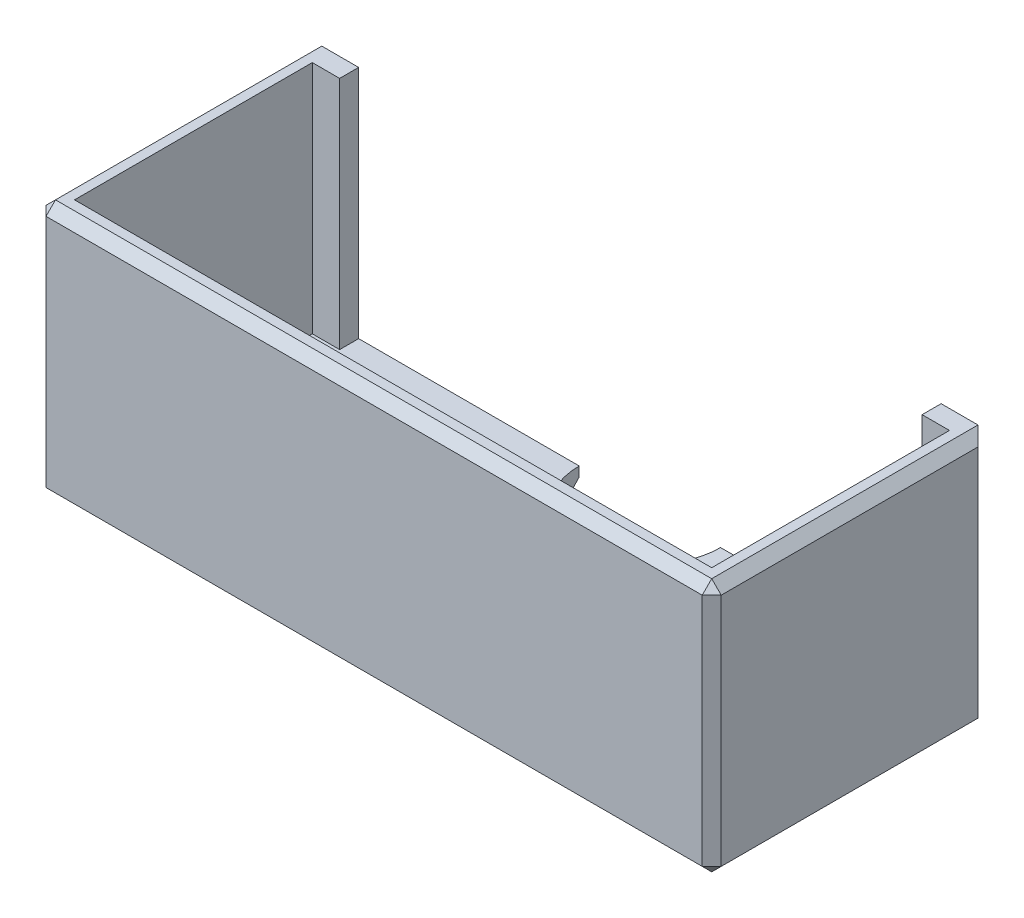
SolidWorks part; units mm, degrees
ref_plane "Front Plane" through (0, 0, 0) normal (0, 0, 1) x (1, 0, 0)
ref_plane "Top Plane" through (0, 0, 0) normal (0, 1, 0) x (1, 0, 0)
ref_plane "Right Plane" through (0, 0, 0) normal (1, 0, 0) x (0, 0, -1)
sketch "Sketch1" plane through (0, 0, 0) normal (0, 1, 0) x (1, 0, 0)
  line L1 (-33.5, -12.5) -> (33.5, -12.5)
  line L2 (-33.5, -12.5) -> (-33.5, 12.5)
  line L3 (-33.5, 12.5) -> (33.5, 12.5)
  line L4 (33.5, -12.5) -> (33.5, 12.5)
  line L5 (-33.5, -12.5) -> (33.5, 12.5) construction
  line L6 (-33.5, 12.5) -> (33.5, -12.5) construction
  point P0 (0, 0)
  dimension "D1" = 67
  dimension "D2" = 25
extrude "Extrude-Thin1" add sketch "Sketch1" against normal blind 24.7 thin
sketch "Sketch2" plane through (0, 0, 0) normal (0, 1, 0) x (1, 0, 0)
  line L0 (33.5, 12.5) -> (-33.5, 12.5) construction
  line L1 (-30.6233, 4.165) -> (30.6233, 4.165)
  line L2 (-30.6233, 4.165) -> (-30.6233, 20.835)
  line L3 (-30.6233, 20.835) -> (30.6233, 20.835)
  line L4 (30.6233, 4.165) -> (30.6233, 20.835)
  line L5 (-30.6233, 4.165) -> (30.6233, 20.835) construction
  line L6 (-30.6233, 20.835) -> (30.6233, 4.165) construction
  point P0 (0, 12.5)
extrude "Cut-Extrude1" cut sketch "Sketch2" against normal through all both and the other way through all
sketch "Sketch3" plane through (0, -24.7, 0) normal (0, -1, 0) x (1, 0, 0)
  line L0 (35.5, 14.5) -> (35.5, -14.5)
  line L12 (33.5, -12.5) -> (30.6233, -12.5)
  line L13 (30.6233, -12.5) -> (30.6233, -14.5)
  line L14 (30.6233, -14.5) -> (35.5, -14.5)
  line L15 (35.5, -14.5) -> (35.5, 14.5)
  line L16 (35.5, 14.5) -> (-35.5, 14.5)
  line L17 (-35.5, 14.5) -> (-35.5, -14.5)
  line L18 (-35.5, -14.5) -> (-30.6233, -14.5)
  line L19 (-30.6233, -14.5) -> (-30.6233, -12.5)
  line L20 (-30.6233, -12.5) -> (-33.5, -12.5)
  line L21 (-33.5, -12.5) -> (-33.5, 12.5)
  line L22 (-33.5, 12.5) -> (33.5, 12.5)
  line L23 (33.5, 12.5) -> (33.5, -12.5)
  line L26 (30.6233, -14.5) -> (35.5, -14.5)
  line L28 (35.5, 14.5) -> (-35.5, 14.5)
  line L29 (-35.5, 14.5) -> (-35.5, -14.5)
  line L30 (-35.5, -14.5) -> (35.5, -14.5)
  circle A0 centre (0, -14.5) radius 7.43
  line M1 (33.5, -12.5) -> (30.6233, -12.5)
  line M2 (30.6233, -12.5) -> (30.6233, -14.5)
  line M3 (30.6233, -14.5) -> (35.5, -14.5)
  line M4 (35.5, -14.5) -> (35.5, 14.5)
  line M5 (35.5, 14.5) -> (-35.5, 14.5)
  line M6 (-35.5, 14.5) -> (-35.5, -14.5)
  line M7 (-35.5, -14.5) -> (-30.6233, -14.5)
  line M8 (-30.6233, -14.5) -> (-30.6233, -12.5)
  line M9 (-30.6233, -12.5) -> (-33.5, -12.5)
  line M10 (-33.5, -12.5) -> (-33.5, 12.5)
  line M11 (-33.5, 12.5) -> (33.5, 12.5)
  line M12 (33.5, 12.5) -> (33.5, -12.5)
  dimension "D2" = 14.86
  dimension "D1" = 0
extrude "Boss-Extrude1" add sketch "Sketch3" along normal blind 2 contours A0 L30 M2 M1 M12 M11 M10 M9 M8 | M12 M1 M2 M3 M4 M5 M6 M7 M8 M9 M10 M11
chamfer "Chamfer1" distance 1 angle 45 12 edges at (0, 0, 14.5) (-35.5, 0, 0) (35.5, 0, 0) (21.465, -26.7, -14.5) (35.5, -26.7, 0) (0, -26.7, 14.5) (-35.5, -26.7, 0) (-21.465, -26.7, -14.5) (35.5, -13.35, 14.5) (-35.5, -13.35, 14.5) (-35.5, -13.35, -14.5) (35.5, -13.35, -14.5)
